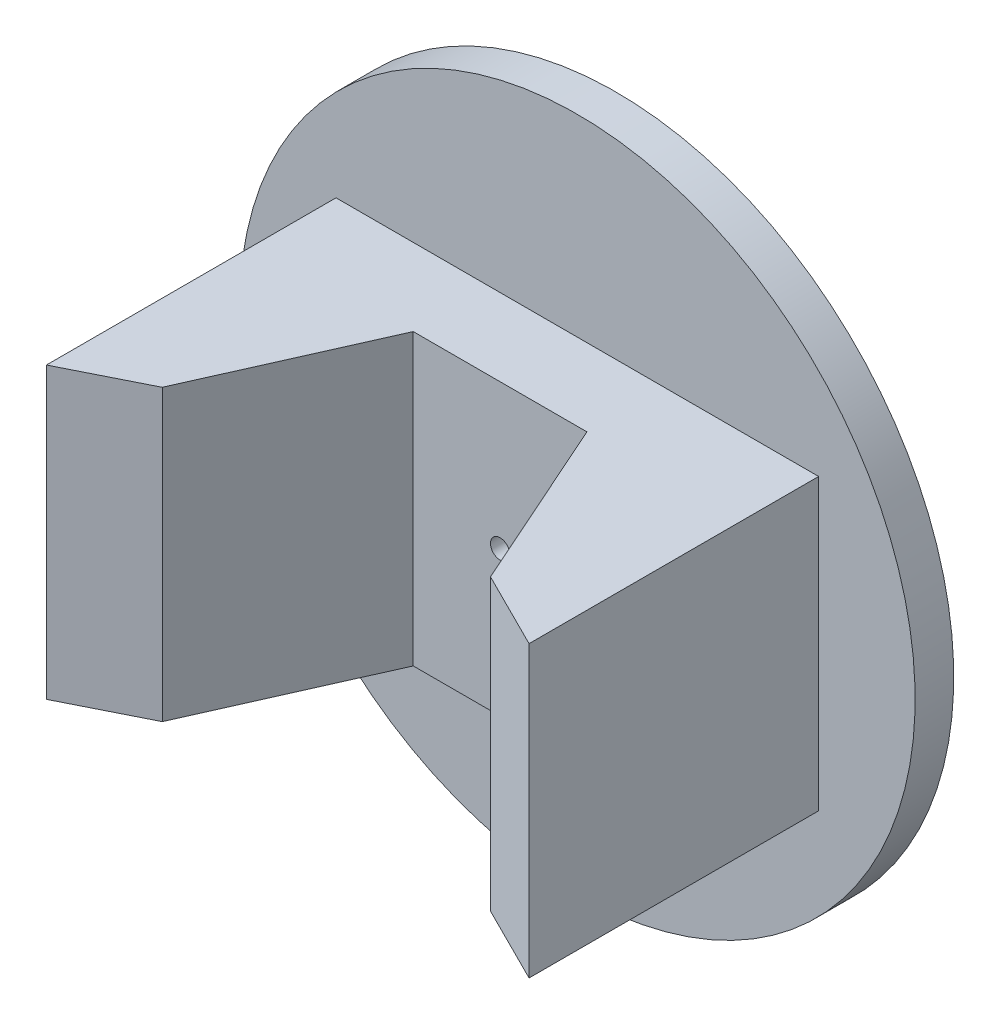
SolidWorks part; units mm, degrees
ref_plane "Alzado" through (0, 0, 0) normal (0, 0, 1) x (1, 0, 0)
ref_plane "Planta" through (0, 0, 0) normal (0, 1, 0) x (1, 0, 0)
ref_plane "Vista lateral" through (0, 0, 0) normal (1, 0, 0) x (0, 0, -1)
sketch "Croquis1" plane through (0, 0, 0) normal (0, 1, 0) x (1, 0, 0)
  line L0 (8.5, -13) -> (4.5, -4)
  line L1 (12.5, 0) -> (12.5, -15)
  line L2 (-12.5, 0) -> (12.5, 0)
  line L3 (12.5, -15) -> (8.5, -13)
  line L6 (4.5, -4) -> (-4.5, -4)
  line L7 (-12.5, 0) -> (-12.5, -15)
  line L8 (-4.5, -4) -> (-8.5, -13)
  line L9 (-8.5, -13) -> (-12.5, -15)
  dimension "D5" = 8
  dimension "D1" = 25
  dimension "D2" = 15
  dimension "D3" = 15
  dimension "D4" = 8
  dimension "D6" = 4
  dimension "D7" = 4
  dimension "D8" = 4
  dimension "D9" = 2
  dimension "D10" = 2
extrude "Saliente-Extruir1" add sketch "Croquis1" along normal blind 15
sketch "Croquis3" plane through (0, 0, 0) normal (0, 0, -1) x (-1, 0, 0)
  line L0 (12.5, 0) -> (-12.5, 15) construction
  line L1 (12.5, 15) -> (-12.5, 0) construction
  circle A0 centre (0, 7.5) radius 17.5
  dimension "D1" = 35
extrude "Saliente-Extruir2" add sketch "Croquis3" along normal blind 2
sketch "Croquis4" plane through (0, 0, -2) normal (0, 0, -1) x (-1, 0, 0)
  circle A0 centre (0, 7.5) radius 10
  dimension "D1" = 20
extrude "Saliente-Extruir3" add sketch "Croquis4" along normal blind 3
ref_axis "Eje1" through (0, 7.5, -5) along (0, 0, 1)
ref_plane "Plano1" through (0, 0, 0) normal (1, 0, 0) x (0, 0, -1)
sketch "Croquis6" plane through (0, 0, 0) normal (1, 0, 0) x (0, 0, -1)
  line L0 (5, 17.5) -> (2, 17.5) construction
  line L1 (5, -2.5) -> (5, 17.5) construction
  circle A0 centre (3.5, 17.5) radius 0.75
  dimension "D1" = 1.5
  dimension "D2" = 1.5
revolve "Cortar-Revolución1" cut sketch "Croquis6" angle 360 about axis through (0, 7.5, -5) along (0, 0, 1)
sketch "Croquis7" plane through (0, 0, -5) normal (0, 0, -1) x (-1, 0, 0)
  circle A0 centre (0, 7.5) radius 5
  dimension "D1" = 10
extrude "Saliente-Extruir4" add sketch "Croquis7" along normal blind 3
sketch "Croquis8" plane through (0, 0, -8) normal (0, 0, -1) x (-1, 0, 0)
  circle A0 centre (0, 7.5) radius 0.5
  dimension "D1" = 1
extrude "Cortar-Extruir2" cut sketch "Croquis8" against normal through all
